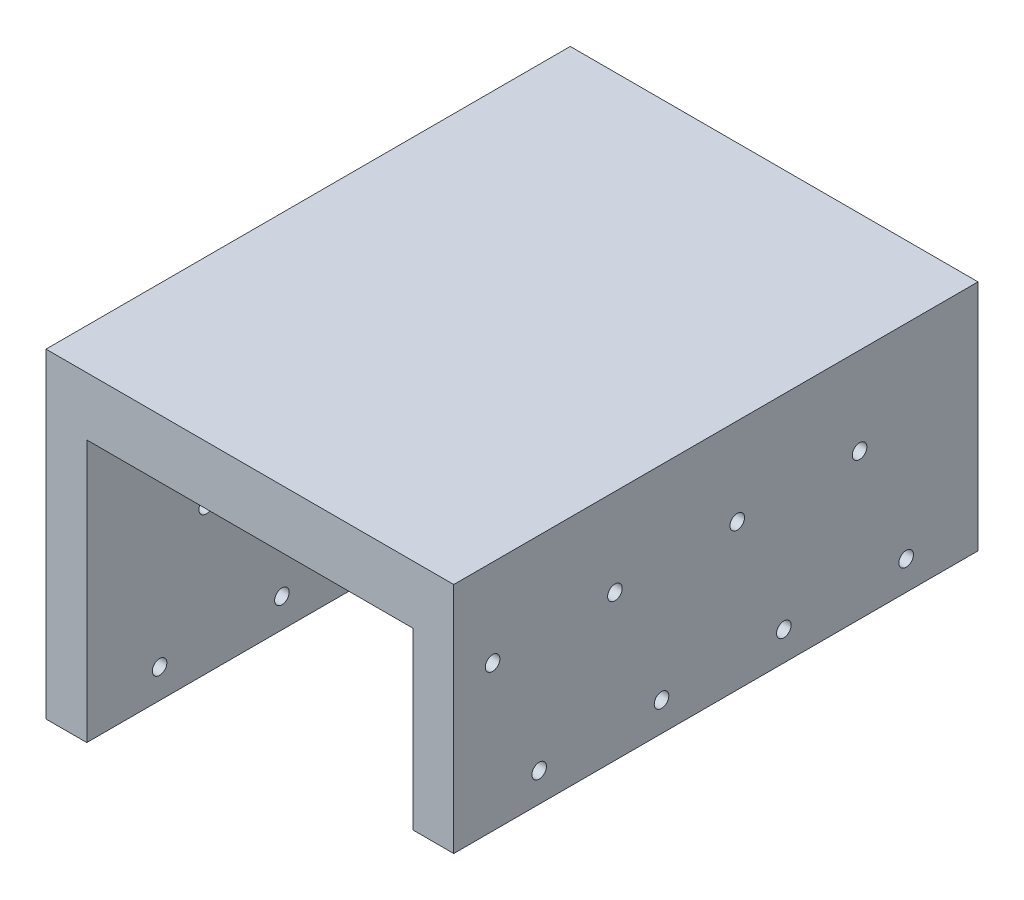
SolidWorks part; units mm, degrees
ref_plane "Front Plane" through (0, 0, 0) normal (0, 0, 1) x (1, 0, 0)
ref_plane "Top Plane" through (0, 0, 0) normal (0, 1, 0) x (1, 0, 0)
ref_plane "Right Plane" through (0, 0, 0) normal (1, 0, 0) x (0, 0, -1)
sketch "Sketch1" plane through (0, 0, 0) normal (0, 0, 1) x (1, 0, 0)
  line L1 (0, 0) -> (70, 0)
  line L2 (0, 0) -> (0, 55)
  line L3 (0, 55) -> (70, 55)
  line L4 (70, 0) -> (70, 55)
  dimension "D1" = 70
  dimension "D2" = 55
extrude "Boss-Extrude1" add sketch "Sketch1" along normal blind 90
sketch "Sketch2" plane through (0, 0, 90) normal (0, 0, 1) x (1, 0, 0)
  line L0 (7, 0) -> (7, 45)
  line L1 (0, 0) -> (70, 0) construction
  line L2 (7, 45) -> (63, 45)
  line L3 (63, 45) -> (63, 15)
  line L4 (60, 0) -> (7, 0)
  line L5 (0, 55) -> (0, 0) construction
  line L6 (70, 0) -> (70, 55) construction
  line L7 (70, 55) -> (0, 55) construction
  line L8 (63, 15) -> (70, 15)
  line L9 (70, 15) -> (70, 0)
  line L10 (70, 0) -> (60, 0)
  dimension "D1" = 7
  dimension "D2" = 7
  dimension "D3" = 10
  dimension "D4" = 15
extrude "Cut-Extrude1" cut sketch "Sketch2" against normal through all both and the other way through all
sketch "Sketch3" plane through (0, 0, 0) normal (-1, 0, 0) x (0, 0, 1)
  line L0 (90, 0) -> (0, 0) construction
  line L1 (0, 55) -> (0, 0) construction
  circle A0 centre (6.5, 25) radius 1.25
  circle A1 centre (14.5, 5) radius 1.25
  circle A2 centre (27.5, 25) radius 1.25
  circle A3 centre (35.5, 5) radius 1.25
  circle A4 centre (48.5, 25) radius 1.25
  circle A5 centre (56.5, 5) radius 1.25
  circle A6 centre (69.5, 25) radius 1.25
  circle A7 centre (77.5, 5) radius 1.25
  dimension "D2" = 2.5
  dimension "D3" = 2.5
  dimension "D7" = 2.5
  dimension "D8" = 2.5
  dimension "D13" = 2.5
  dimension "D14" = 2.5
  dimension "D17" = 2.5
  dimension "D18" = 2.5
  dimension "D1" = 5
  dimension "D4" = 8
  dimension "D5" = 20
  dimension "D6" = 6.5
  dimension "D9" = 8
  dimension "D10" = 20
  dimension "D11" = 5
  dimension "D12" = 13
  dimension "D15" = 8
  dimension "D16" = 20
  dimension "D19" = 8
  dimension "D20" = 20
  dimension "D21" = 13
  dimension "D22" = 5
  dimension "D23" = 5
  dimension "D24" = 13
sketch "Sketch4" plane through (70, 0, 0) normal (1, 0, 0) x (0, 0, -1)
  line L0 (0, 15) -> (-90, 15) construction
  circle A0 centre (-83.3318, 40) radius 1.25
  circle A1 centre (-75.3318, 20) radius 1.25
  circle A2 centre (-62.3318, 40) radius 1.25
  circle A3 centre (-54.3318, 20) radius 1.25
  circle A4 centre (-41.3318, 40) radius 1.25
  circle A5 centre (-33.3318, 20) radius 1.25
  circle A6 centre (-20.3318, 40) radius 1.25
  circle A7 centre (-12.3318, 20) radius 1.25
  dimension "D1" = 2.5
  dimension "D2" = 2.5
  dimension "D5" = 2.5
  dimension "D6" = 2.5
  dimension "D10" = 2.5
  dimension "D11" = 2.5
  dimension "D14" = 2.5
  dimension "D15" = 2.5
  dimension "D3" = 8
  dimension "D4" = 20
  dimension "D7" = 8
  dimension "D8" = 20
  dimension "D9" = 13
  dimension "D12" = 8
  dimension "D13" = 20
  dimension "D16" = 8
  dimension "D17" = 20
  dimension "D18" = 13
  dimension "D19" = 13
  dimension "D20" = 5
  dimension "D21" = 5
  dimension "D22" = 5
  dimension "D23" = 5
extrude "Cut-Extrude2" cut sketch "Sketch3" against normal up to surface (7 mm away) up to face at (7, 22.5, 45)
extrude "Cut-Extrude4" cut sketch "Sketch4" against normal up to surface (7 mm away) up to face at (63, 30, 45)
